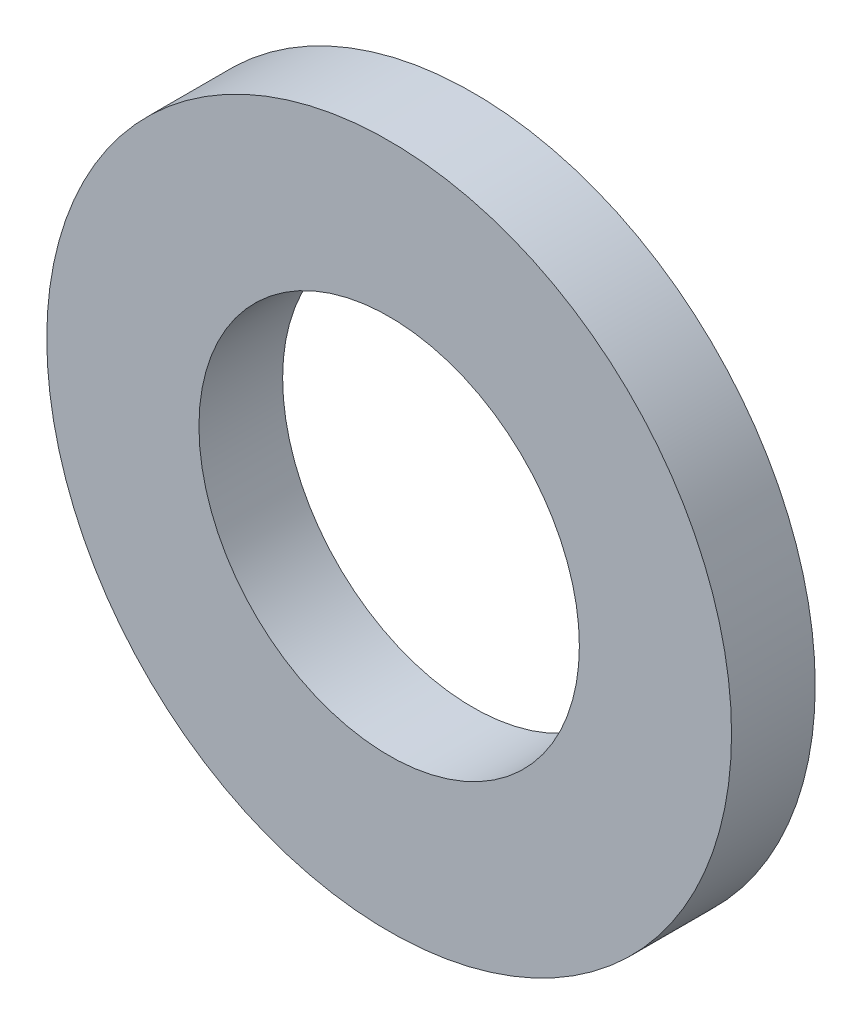
SolidWorks part; units mm, degrees
ref_plane "Front Plane" through (0, 0, 0) normal (0, 0, 1) x (1, 0, 0)
ref_plane "Top Plane" through (0, 0, 0) normal (0, 1, 0) x (1, 0, 0)
ref_plane "Right Plane" through (0, 0, 0) normal (1, 0, 0) x (0, 0, -1)
sketch "Sketch1" plane through (0, 0, 0) normal (0, 0, 1) x (1, 0, 0)
  circle A0 centre (0, 0) radius 22.5
  circle A1 centre (0, 0) radius 12.5
  dimension "D1" = 45
  dimension "D2" = 10
extrude "Boss-Extrude1" add sketch "Sketch1" along normal blind 5.5
